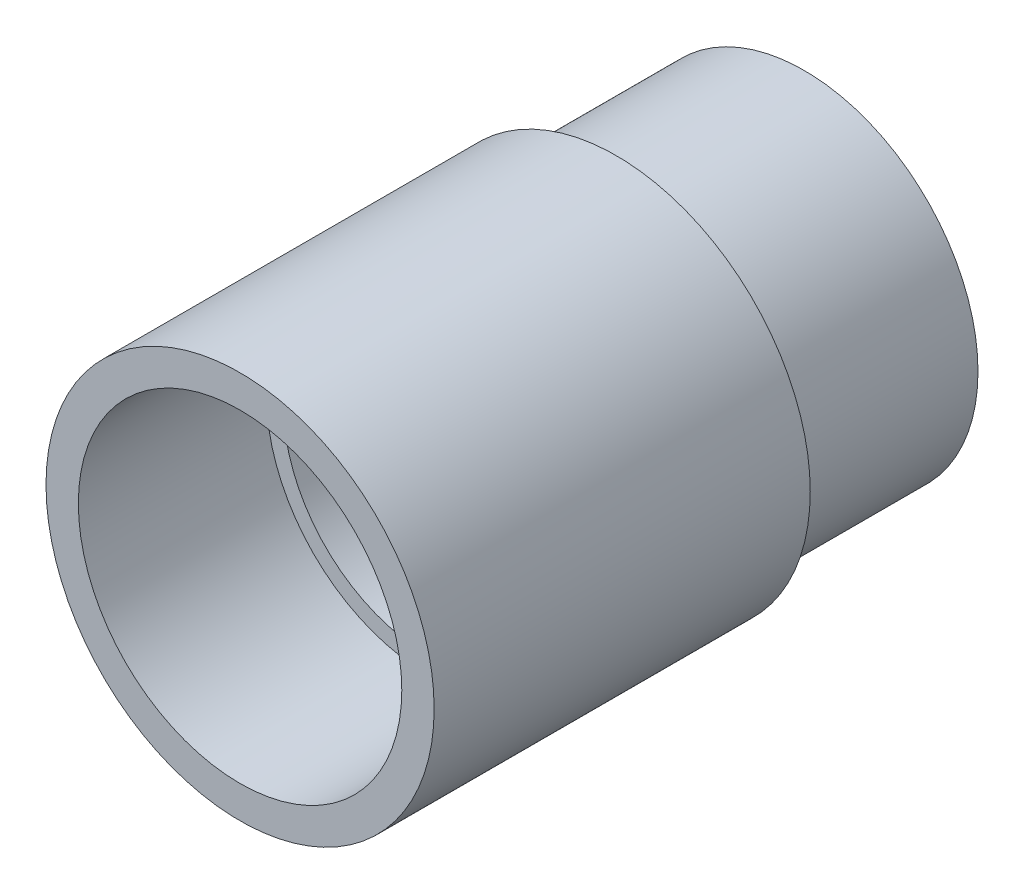
SolidWorks part; units mm, degrees
ref_plane "Front Plane" through (0, 0, 0) normal (0, 0, 1) x (1, 0, 0)
ref_plane "Top Plane" through (0, 0, 0) normal (0, 1, 0) x (1, 0, 0)
ref_plane "Right Plane" through (0, 0, 0) normal (1, 0, 0) x (0, 0, -1)
sketch "Sketch4" plane through (0, 0, 0) normal (0, 0, 1) x (1, 0, 0)
  circle A0 centre (0, 0) radius 15.4
  circle A1 centre (0, 0) radius 18.48
  dimension "D1" = 30.8
  dimension "D2" = 36.96
extrude "Boss-Extrude1" add sketch "Sketch4" along normal blind 40
ref_plane "Plane1" through (0, 0, 20) normal (0, 0, 1) x (1, 0, 0)
sketch "Sketch5" plane through (0, 0, 20) normal (0, 0, 1) x (1, 0, 0)
  circle A0 centre (0, 0) radius 17.2
  circle A1 centre (0, 0) radius 20.64
  dimension "D1" = 34.4
  dimension "D2" = 41.28
extrude "Boss-Extrude2" add sketch "Sketch5" along normal blind 40
